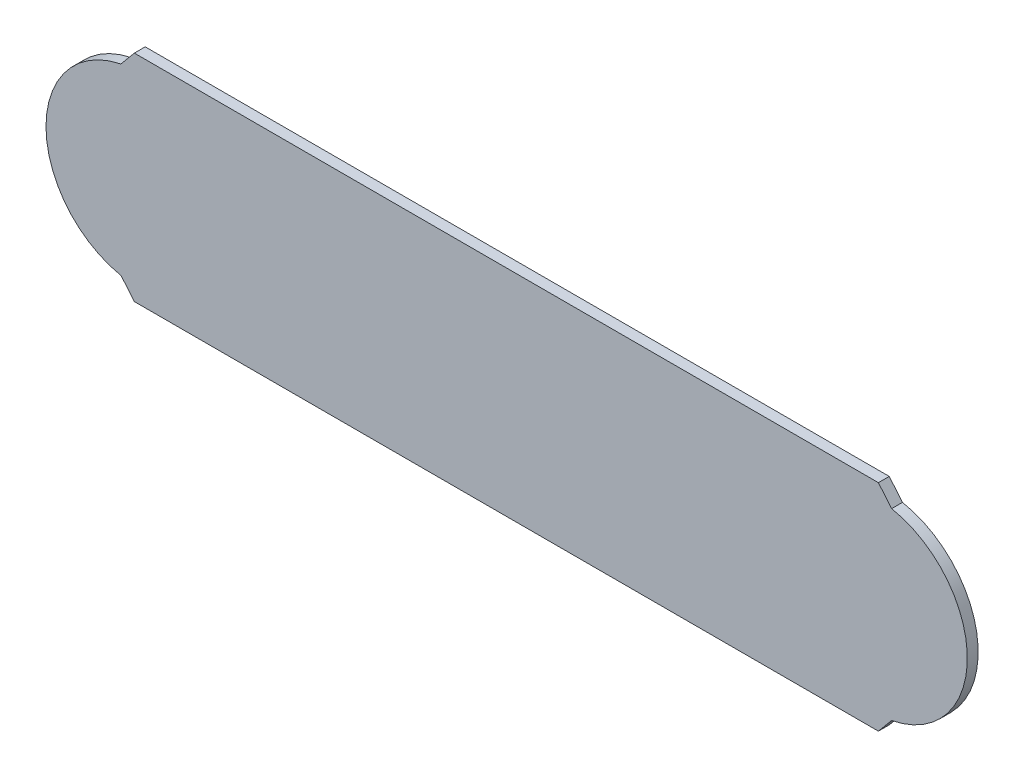
SolidWorks part; units mm, degrees
ref_plane "Front Plane" through (0, 0, 0) normal (0, 0, 1) x (1, 0, 0)
ref_plane "Top Plane" through (0, 0, 0) normal (0, 1, 0) x (1, 0, 0)
ref_plane "Right Plane" through (0, 0, 0) normal (1, 0, 0) x (0, 0, -1)
sketch "Sketch1" plane through (0, 0, 0) normal (0, 0, 1) x (1, 0, 0)
  line L0 (-87.9452, 16.9159) -> (-85.5082, 19.8442)
  line L2 (-85.5082, 19.8442) -> (51.7054, 19.8442)
  line L3 (-85.5082, -19.8442) -> (51.7054, -19.8442)
  line L4 (-87.9452, -16.9159) -> (-85.5082, -19.8442)
  line L10 (54.1425, -16.9159) -> (51.7054, -19.8442)
  line L11 (54.1425, 16.9159) -> (51.7054, 19.8442)
  arc A2 (-87.9452, 16.9159) -> (-88.01, 16.8616) centre (-88.1265, 17.0668) cw
  arc A4 (-87.9452, -16.9159) -> (-88.01, 16.8616) centre (-84.5717, -0.0206) cw
  arc A5 (54.1425, -16.9159) -> (54.1425, 16.9159) centre (50.8737, 0) ccw
  point P27 (-42.7541, -19.8442)
extrude "Boss-Extrude1" add sketch "Sketch1" along normal blind 2
scale "Scale1" scale about centroid uniform scaling yes scale factor 0.6
